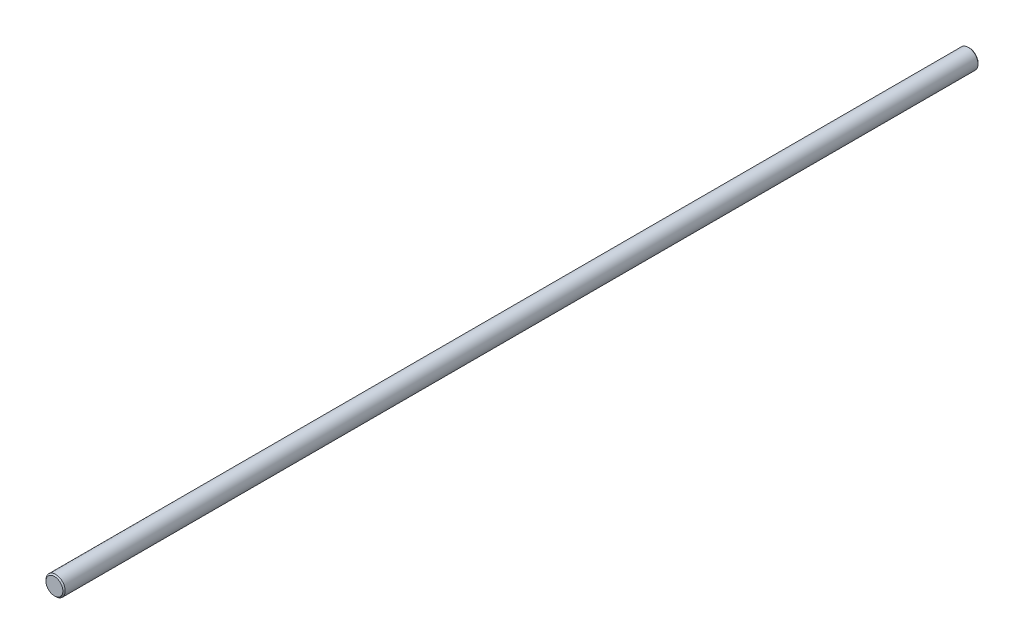
SolidWorks part; units mm, degrees
ref_plane "Front Plane" through (0, 0, 0) normal (0, 0, 1) x (1, 0, 0)
ref_plane "Top Plane" through (0, 0, 0) normal (0, 1, 0) x (1, 0, 0)
ref_plane "Right Plane" through (0, 0, 0) normal (1, 0, 0) x (0, 0, -1)
sketch "Sketch1" plane through (0, 0, 0) normal (0, 0, 1) x (1, 0, 0)
  circle A0 centre (0, 0) radius 4
  dimension "D1" = 8
extrude "Extrude1" add sketch "Sketch1" along normal blind 380
chamfer "Chamfer1" distance 0.5 angle 45 2 edges at (4, 0, 0) (4, 0, 380)
